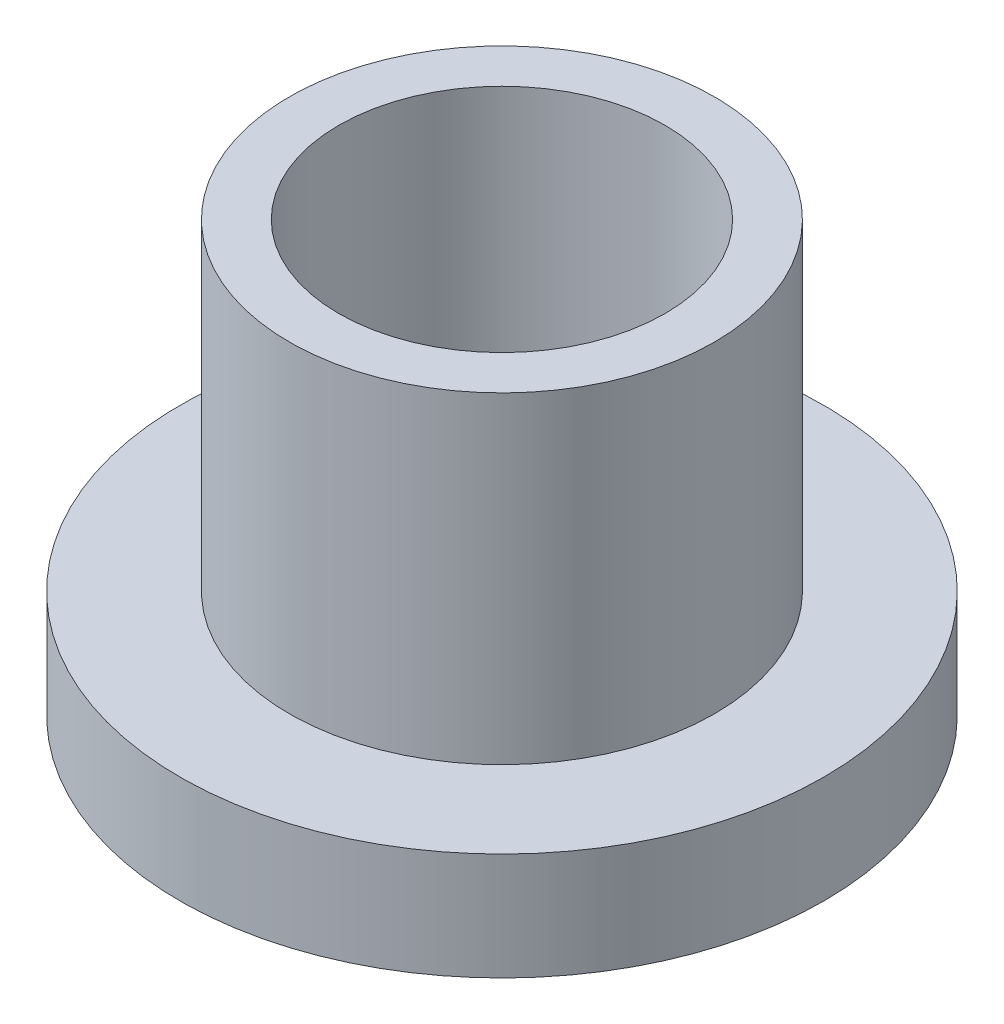
SolidWorks part; units mm, degrees
material "Tin Bearing Bronze"
ref_plane "Front Plane" through (0, 0, 0) normal (0, 0, 1) x (1, 0, 0)
ref_plane "Top Plane" through (0, 0, 0) normal (0, 1, 0) x (1, 0, 0)
ref_plane "Right Plane" through (0, 0, 0) normal (1, 0, 0) x (0, 0, -1)
sketch "Sketch1" plane through (0, 0, 0) normal (0, 0, 1) x (1, 0, 0)
  line L0 (0, 0) -> (0, 25.4) construction
  line L1 (-9.652, 0) -> (-9.652, 25.4)
  line L2 (-9.652, 25.4) -> (-12.573, 25.4)
  line L3 (-12.573, 25.4) -> (-12.573, 6.35)
  line L4 (-12.573, 6.35) -> (-19.05, 6.35)
  line L5 (-19.05, 6.35) -> (-19.05, 0)
  line L6 (-19.05, 0) -> (-9.652, 0)
  dimension "D1" = 25.4
  dimension "D2" = 9.652
  dimension "D3" = 12.573
  dimension "D4" = 19.05
  dimension "D5" = 6.35
revolve "Revolve1" add sketch "Sketch1" angle 360 about L0
